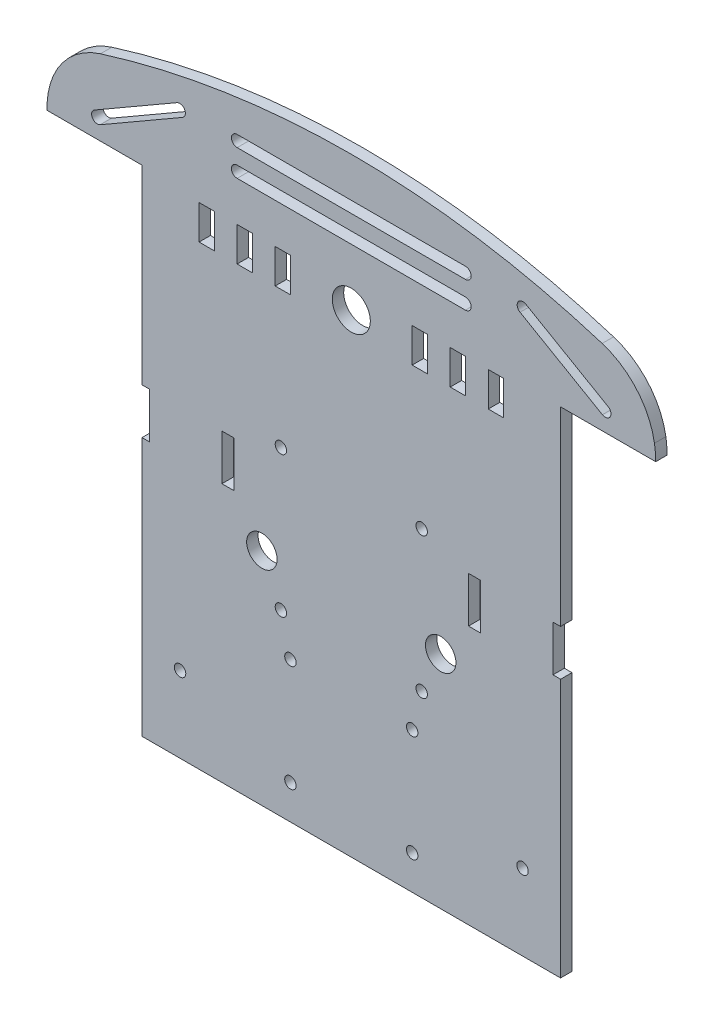
SolidWorks part; units mm, degrees
ref_plane "前视基准面" through (0, 0, 0) normal (0, 0, 1) x (1, 0, 0)
ref_plane "上视基准面" through (0, 0, 0) normal (0, 1, 0) x (1, 0, 0)
ref_plane "右视基准面" through (0, 0, 0) normal (1, 0, 0) x (0, 0, -1)
sketch "草图1" plane through (0, 0, 0) normal (0, 0, 1) x (1, 0, 0)
  line L0 (0, 105) -> (0, -90.7401) construction
  line L1 (55, -55) -> (-55, -55)
  line L2 (-55, -55) -> (-55, 75)
  line L3 (-55, 75) -> (-80, 75)
  line L4 (55, 75) -> (80, 75)
  line L5 (55, -55) -> (55, 75)
  arc A0 (-79.671, 79.0426) -> (-80, 75) centre (-55, 75) ccw
  arc A1 (79.671, 79.0426) -> (80, 75) centre (55, 75) cw
  arc A2 (65.9276, 94.8894) -> (-65.9276, 94.8894) centre (0, -115) ccw
  arc A3 (65.9276, 94.8894) -> (79.671, 79.0426) centre (59.9342, 75.8085) cw
  arc A4 (-79.671, 79.0426) -> (-65.9276, 94.8894) centre (-59.9342, 75.8085) cw
  point P10 (0, -55)
  point P12 (0, 105)
  point P13 (-50, 80)
  dimension "D7" = 20
  dimension "D8" = 20
  dimension "D1" = 110
  dimension "D2" = 130
  dimension "D3" = 25
  dimension "D4" = 55
  dimension "D5" = 30
  dimension "D6" = 220
extrude "凸台-拉伸1" add sketch "草图1" along normal blind 3
sketch "草图2" plane through (0, 0, 0) normal (0, 0, -1) x (-1, 0, 0)
  line L0 (0, 105) -> (0, -60.0492) construction
  line L1 (-30, 94.5) -> (30, 94.5)
  line L2 (-30, 91.5) -> (30, 91.5)
  line L3 (-66.7473, 80) -> (-45.0966, 92.5) construction
  line L4 (-55, 75) -> (-80, 75) construction
  line L5 (-67.4973, 81.299) -> (-45.8466, 93.799)
  line L6 (-65.9973, 78.701) -> (-44.3466, 91.201)
  line L7 (66.7473, 80) -> (45.0966, 92.5) construction
  line L8 (65.9973, 78.701) -> (44.3466, 91.201)
  line L9 (67.4973, 81.299) -> (45.8466, 93.799)
  line L10 (0, 89.5) -> (23.0393, 89.5) construction
  line L11 (0, 74) -> (0, 239.0492) construction
  line L12 (-30, 87.5) -> (30, 87.5)
  line L13 (-30, 84.5) -> (30, 84.5)
  arc A0 (65.9276, 94.8894) -> (-65.9276, 94.8894) centre (0, -115) ccw construction
  arc A1 (-30, 94.5) -> (-30, 91.5) centre (-30, 93) ccw
  arc A2 (30, 94.5) -> (30, 91.5) centre (30, 93) cw
  arc A3 (-67.4973, 81.299) -> (-65.9973, 78.701) centre (-66.7473, 80) ccw
  arc A4 (-44.3466, 91.201) -> (-45.8466, 93.799) centre (-45.0966, 92.5) ccw
  arc A5 (67.4973, 81.299) -> (65.9973, 78.701) centre (66.7473, 80) cw
  arc A6 (44.3466, 91.201) -> (45.8466, 93.799) centre (45.0966, 92.5) cw
  arc A7 (-30, 84.5) -> (-30, 87.5) centre (-30, 86) cw
  arc A8 (30, 84.5) -> (30, 87.5) centre (30, 86) ccw
  dimension "D1" = 3
  dimension "D5" = 3
  dimension "D6" = 3
  dimension "D2" = 60
  dimension "D3" = 12
  dimension "D4" = 30
  dimension "D7" = 25
  dimension "D8" = 5
  dimension "D9" = 2
extrude "切除-拉伸1" cut sketch "草图2" against normal through all
sketch "草图3" plane through (0, 0, 3) normal (0, 0, 1) x (1, 0, 0)
  line L0 (-112.085, 13) -> (112.3231, 13) construction
  line L1 (-80, 75) -> (-55, 75) construction
  line L3 (0, 94.5) -> (0, -90.5861) construction
  line L4 (-30, 94.5) -> (30, 94.5) construction
  line L5 (-55, 13) -> (-53, 13)
  line L6 (-53, 13) -> (-53, 25)
  line L7 (-53, 25) -> (-55, 25)
  line L8 (-55, 75) -> (-55, -55) construction
  line L9 (-55, 13) -> (-55, 25)
  line L10 (-34, 13) -> (-34, 25)
  line L11 (-34, 25) -> (-30.8, 25)
  line L12 (-30.8, 25) -> (-30.8, 13)
  line L13 (-30.8, 13) -> (-34, 13)
  line L14 (30.8, 25) -> (30.8, 13)
  line L15 (34, 25) -> (30.8, 25)
  line L16 (34, 13) -> (34, 25)
  line L17 (55, 13) -> (55, 25)
  line L18 (53, 25) -> (55, 25)
  line L19 (53, 13) -> (53, 25)
  line L20 (30.8, 13) -> (34, 13)
  line L21 (53, 13) -> (55, 13)
  dimension "D1" = 224.4081
  dimension "D2" = 62
  dimension "D3" = 2
  dimension "D4" = 12
  dimension "D5" = 3.2
  dimension "D6" = 12
  dimension "D7" = 19
extrude "切除-拉伸2" cut sketch "草图3" against normal through all
sketch "草图4" plane through (0, 0, 0) normal (0, 0, -1) x (-1, 0, 0)
  line L0 (0, 0) -> (0, 44.334) construction
  circle A0 centre (23.5, 3) radius 4
  circle A1 centre (-23.5, 3) radius 4
  point P8 (19.5, 3)
  dimension "D1" = 8
  dimension "D2" = 10
  dimension "D3" = 47
extrude "切除-拉伸3" cut sketch "草图4" against normal through all
sketch "草图5" plane through (0, 0, 0) normal (0, 0, -1) x (-1, 0, 0)
  line L0 (0, 0) -> (0, 89.367) construction
  line L1 (-55, 69.5) -> (62.7539, 69.5) construction
  line L2 (-40, 74) -> (-36, 74)
  line L3 (-40, 74) -> (-40, 65)
  line L4 (-40, 65) -> (-36, 65)
  line L5 (-36, 74) -> (-36, 65)
  line L6 (-40, 74) -> (-36, 65) construction
  line L7 (-40, 65) -> (-36, 74) construction
  line L8 (-30, 74) -> (-26, 74)
  line L9 (-30, 74) -> (-30, 65)
  line L10 (-30, 65) -> (-26, 65)
  line L11 (-26, 74) -> (-26, 65)
  line L12 (80, 75) -> (55, 75) construction
  line L13 (-30, 74) -> (-26, 65) construction
  line L14 (-30, 65) -> (-26, 74) construction
  line L15 (-20, 74) -> (-16, 74)
  line L16 (-20, 74) -> (-20, 65)
  line L17 (-20, 65) -> (-16, 65)
  line L18 (-16, 74) -> (-16, 65)
  line L20 (-20, 74) -> (-16, 65) construction
  line L21 (-20, 65) -> (-16, 74) construction
  line L22 (20, 74) -> (16, 74)
  line L23 (30, 74) -> (26, 74)
  line L24 (40, 74) -> (36, 74)
  line L25 (20, 65) -> (16, 74) construction
  line L26 (20, 74) -> (16, 65) construction
  line L27 (30, 65) -> (26, 74) construction
  line L28 (30, 74) -> (26, 65) construction
  line L29 (40, 65) -> (36, 74) construction
  line L30 (40, 74) -> (36, 65) construction
  line L31 (16, 74) -> (16, 65)
  line L32 (20, 65) -> (16, 65)
  line L33 (20, 74) -> (20, 65)
  line L34 (26, 74) -> (26, 65)
  line L35 (30, 65) -> (26, 65)
  line L36 (30, 74) -> (30, 65)
  line L37 (36, 74) -> (36, 65)
  line L38 (40, 65) -> (36, 65)
  line L39 (40, 74) -> (40, 65)
  line L40 (-55, 25) -> (-55, 75) construction
  circle A0 centre (0, 69.5) radius 5
  point P3 (-38, 69.5)
  point P8 (-28, 69.5)
  point P19 (-18, 69.5)
  dimension "D5" = 10
  dimension "D1" = 9
  dimension "D2" = 4
  dimension "D4" = 15
  dimension "D6" = 10
  dimension "D3" = 3
extrude "切除-拉伸4" cut sketch "草图5" against normal through all
sketch "草图6" plane through (0, 0, 0) normal (0, 0, -1) x (-1, 0, 0)
  line L0 (30.8, 25) -> (34, 25) construction
  line L1 (-18.5, -8) -> (18.5, -8) construction
  line L2 (-18.5, -8) -> (-18.5, 29) construction
  line L3 (-18.5, 29) -> (18.5, 29) construction
  line L4 (18.5, -8) -> (18.5, 29) construction
  line L5 (-18.5, -8) -> (18.5, 29) construction
  line L6 (-18.5, 29) -> (18.5, -8) construction
  circle A0 centre (18.5, 29) radius 1.5
  circle A1 centre (18.5, -8) radius 1.5
  circle A2 centre (-18.5, -8) radius 1.5
  circle A3 centre (-18.5, 29) radius 1.5
  point P0 (0, 10.5)
  dimension "D3" = 3
  dimension "D4" = 3
  dimension "D5" = 3
  dimension "D6" = 3
  dimension "D1" = 37
  dimension "D2" = 37
  dimension "D7" = 4
extrude "切除-拉伸5" cut sketch "草图6" against normal blind 10
sketch "草图8" plane through (0, 0, 0) normal (0, 0, -1) x (-1, 0, 0)
  line L1 (-16, -18) -> (16, -18) construction
  line L2 (-16, -18) -> (-16, -46) construction
  line L3 (-16, -46) -> (16, -46) construction
  line L4 (16, -18) -> (16, -46) construction
  line L5 (-16, -18) -> (16, -46) construction
  line L6 (-16, -46) -> (16, -18) construction
  circle A0 centre (-16, -46) radius 1.5
  circle A1 centre (-16, -18) radius 1.5
  circle A2 centre (16, -18) radius 1.5
  circle A3 centre (16, -46) radius 1.5
  circle A4 centre (-18.5, -8) radius 1.5 construction
  point P0 (0, -32)
  dimension "D3" = 3
  dimension "D4" = 3
  dimension "D5" = 3
  dimension "D6" = 3
  dimension "D1" = 32
  dimension "D2" = 28
  dimension "D7" = 10
extrude "切除-拉伸7" cut sketch "草图8" against normal through all
sketch "草图9" plane through (0, 0, 0) normal (0, 0, -1) x (-1, 0, 0)
  line L4 (55, 13) -> (55, -55) construction
  line L5 (55, -55) -> (-55, -55) construction
  line L6 (-55, -55) -> (-55, 13) construction
  circle A2 centre (-45, -35) radius 1.5
  circle A4 centre (45, -35) radius 1.5
  point P0 (45.2329, -33.5424)
  dimension "D1" = 3
  dimension "D2" = 10
  dimension "D3" = 20
  dimension "D4" = 3
  dimension "D5" = 20
  dimension "D6" = 10
extrude "切除-拉伸8" cut sketch "草图9" against normal through all contours A2 | A4
